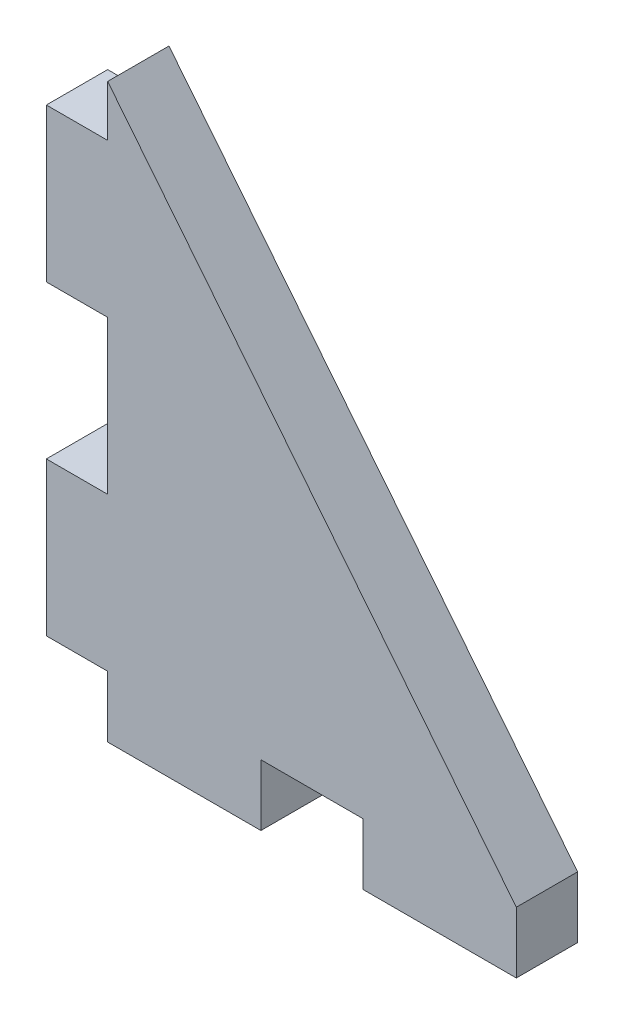
SolidWorks part; units mm, degrees
material "6061-T6 (SS)"
ref_plane "Alzado" through (0, 0, 0) normal (0, 0, 1) x (1, 0, 0)
ref_plane "Planta" through (0, 0, 0) normal (0, 1, 0) x (1, 0, 0)
ref_plane "Vista lateral" through (0, 0, 0) normal (1, 0, 0) x (0, 0, -1)
sketch "Croquis1" plane through (0, 0, 0) normal (0, 0, 1) x (1, 0, 0)
  line L0 (0, 15) -> (0, 30)
  line L1 (0, 50) -> (40, 0)
  line L2 (25, 0) -> (15, 0)
  line L3 (0, 45) -> (0, 50)
  line L4 (0, 0) -> (-6, 0)
  line L6 (0, 15) -> (-6, 15)
  line L7 (-6, 0) -> (-6, 15)
  line L8 (0, 45) -> (-6, 45)
  line L10 (0, 30) -> (-6, 30)
  line L11 (-6, 45) -> (-6, 30)
  line L14 (0, 0) -> (0, -6)
  line L15 (0, -6) -> (15, -6)
  line L16 (15, 0) -> (15, -6)
  line L18 (25, 0) -> (25, -6)
  line L19 (25, -6) -> (40, -6)
  line L20 (40, 0) -> (40, -6)
  dimension "D1" = 40
  dimension "D2" = 6
  dimension "D3" = 15
  dimension "D4" = 15
  dimension "D5" = 50
  dimension "D6" = 15
  dimension "D7" = 10
  dimension "D8" = 6
extrude "Saliente-Extruir1" add sketch "Croquis1" along normal mid plane 6
